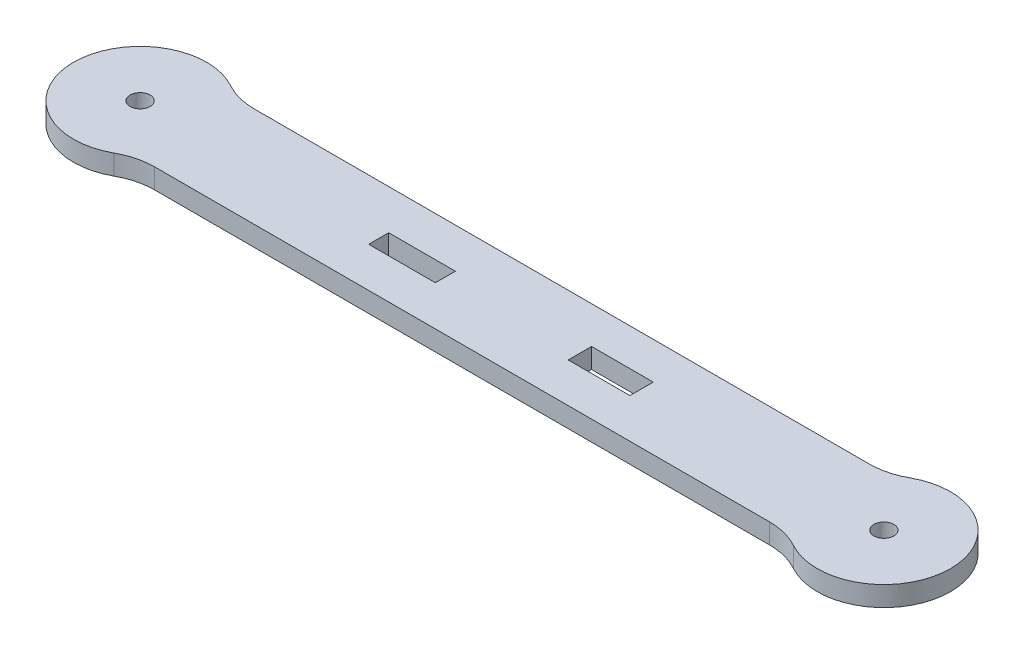
SolidWorks part; units mm, degrees
ref_plane "前视基准面" through (0, 0, 0) normal (0, 0, 1) x (1, 0, 0)
ref_plane "上视基准面" through (0, 0, 0) normal (0, 1, 0) x (1, 0, 0)
ref_plane "右视基准面" through (0, 0, 0) normal (1, 0, 0) x (0, 0, -1)
sketch "草图1" plane through (0, 0, 0) normal (0, 1, 0) x (1, 0, 0)
  line L0 (-120.37, 0) -> (120.37, 0) construction
  line L1 (0, 79.1414) -> (0, -79.1414) construction
  line L2 (-49.1912, -7.5) -> (49.1912, -7.5)
  line L3 (-49.1912, 7.5) -> (49.1912, 7.5)
  line L5 (-20, 1.5) -> (-10, 1.5)
  line L6 (-20, 1.5) -> (-20, -1.5)
  line L7 (-20, -1.5) -> (-10, -1.5)
  line L8 (-10, 1.5) -> (-10, -1.5)
  line L9 (10, 1.9394) -> (19.2592, 1.9394)
  line L10 (10, 1.9394) -> (10, -1.5641)
  line L11 (10, -1.5641) -> (19.2592, -1.5641)
  line L12 (19.2592, 1.9394) -> (19.2592, -1.5641)
  arc A0 (-49.1912, 7.5) -> (-49.1912, -7.5) centre (-55.8056, 0) ccw
  arc A1 (49.1912, -7.5) -> (49.1912, 7.5) centre (55.8056, 0) ccw
  circle A2 centre (-55.8056, 0) radius 1.5
  circle A3 centre (55.8056, 0) radius 1.5
  point P4 (0, 0)
  point P8 (0, 0)
  dimension "D1" = 10
  dimension "D3" = 3
  dimension "D2" = 15
  dimension "D4" = 10
  dimension "D5" = 3
  dimension "D6" = 20
extrude "凸台-拉伸1" add sketch "草图1" along normal blind 3
fillet "圆角1" radius 10 4 edges at (49.1912, 1.5, 7.5) (-49.1912, 1.5, 7.5) (49.1912, 1.5, -7.5) (-49.1912, 1.5, -7.5)
